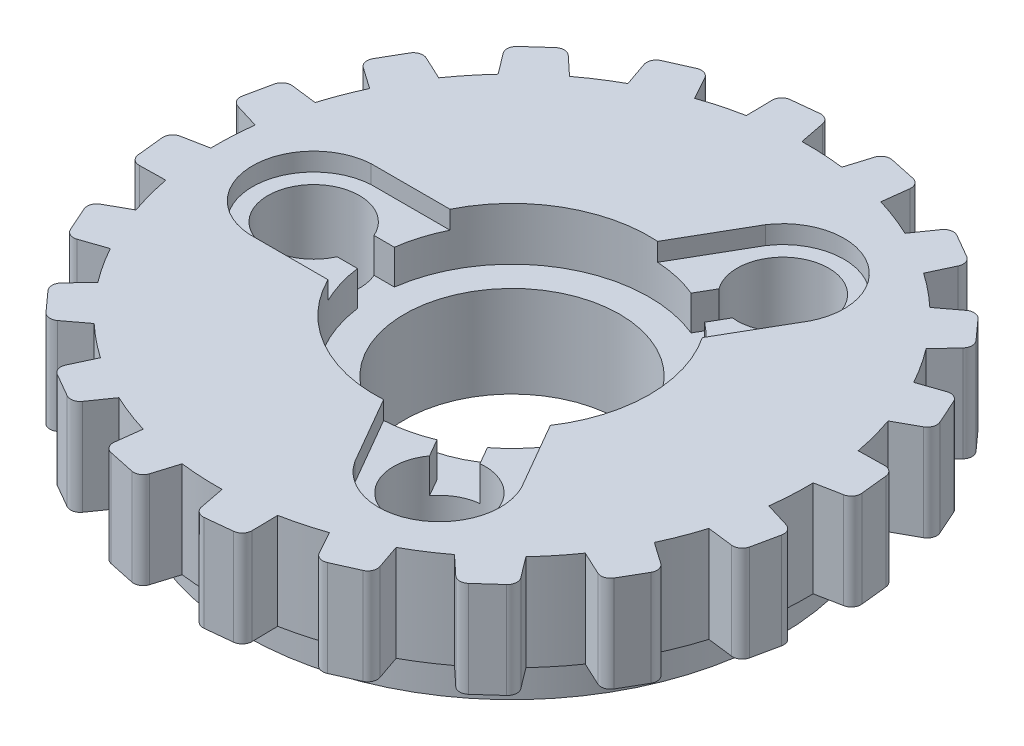
SolidWorks part; units mm, degrees
ref_plane "Front Plane" through (0, 0, 0) normal (0, 0, 1) x (1, 0, 0)
ref_plane "Top Plane" through (0, 0, 0) normal (0, 1, 0) x (1, 0, 0)
ref_plane "Right Plane" through (0, 0, 0) normal (1, 0, 0) x (0, 0, -1)
sketch "Sketch2" plane through (0, 0, 0) normal (0, 1, 0) x (1, 0, 0)
  circle A0 centre (0, 0) radius 30.764
  circle A1 centre (-20.6375, 0) radius 4.7625
  circle A2 centre (10.3187, 17.8726) radius 4.7625
  circle A3 centre (10.3187, -17.8726) radius 4.7625
  circle A5 centre (0, 0) radius 11.2
  point P11 (0, 0)
  dimension "D2" = 3
  dimension "D1" = 22.4
  dimension "D4" = 61.528
  dimension "D5" = 9.525
  dimension "D3" = 20.6375
extrude "Boss-Extrude2" add sketch "Sketch2" along normal blind 10
sketch "Sketch4" plane through (0, 0, 0) normal (0, -1, 0) x (1, 0, 0)
  circle A0 centre (10.3187, 17.8726) radius 4.7625 construction
  circle A1 centre (10.3187, 17.8726) radius 4.7625
  circle A2 centre (0, 0) radius 11.2
  circle A19 centre (0, 0) radius 27.7625
  point P6 (-1.3086, -0.0126)
  point P13 (12.187, -21.1085)
  point P15 (-24.374, 0)
  point P17 (12.187, 21.1085)
  point P18 (-12.5475, 0)
  point P25 (16.9495, -21.1085)
  point P26 (16.9495, 21.1085)
  point P27 (-26.7552, 4.1244)
  point P28 (9.8057, 25.2329)
  point P29 (9.8057, -25.2329)
  point P30 (-26.7552, -4.1244)
  point P31 (16.4175, -16.723)
  point P36 (16.4175, 16.723)
  point P46 (13.9118, 4.2533)
  circle M1 centre (10.3187, -17.8726) radius 4.7625
  circle M2 centre (-20.6375, 0) radius 4.7625
  circle M4 centre (0, 0) radius 11.2
  circle M5 centre (10.3187, 17.8726) radius 4.7625
  dimension "D1" = 22.4
extrude "Boss-Extrude3" add sketch "Sketch4" along normal blind 5 contours A19 M1 M5 M4 M2
sketch "Sketch5" plane through (0, 10, 0) normal (0, 1, 0) x (1, 0, 0)
  line L0 (-21, 6.35) -> (-9.2259, 6.35)
  line L1 (-21, -6.35) -> (-9.2259, -6.35)
  line L2 (5.0007, 21.3615) -> (-0.8863, 11.1649)
  line L3 (15.9993, 15.0115) -> (10.1122, 4.8149)
  line L4 (15.9993, -15.0115) -> (10.1122, -4.8149)
  line L5 (5.0007, -21.3615) -> (-0.8863, -11.1649)
  arc A2 (15.9993, 15.0115) -> (5.0007, 21.3615) centre (10.3188, 17.8726) ccw
  arc A4 (-21, 6.35) -> (-21, -6.35) centre (-20.6375, 0) ccw
  arc A5 (10.1122, 4.8149) -> (-0.8863, 11.1649) centre (0, 0) ccw
  circle A8 centre (-20.6375, 0) radius 4.7625 construction
  circle A10 centre (0, 0) radius 11.2 construction
  arc A11 (-9.2259, 6.35) -> (-9.2259, -6.35) centre (0, 0) ccw
  arc A12 (5.0007, -21.3615) -> (15.9993, -15.0115) centre (10.3187, -17.8726) ccw
  arc A13 (-0.8863, -11.1649) -> (10.1122, -4.8149) centre (0, 0) ccw
  point P9 (0, 0)
  point P23 (0, 0)
  dimension "D1" = 3
extrude "Cut-Extrude4" cut sketch "Sketch5" against normal blind 1.8875
sketch "Sketch7" plane through (0, 10, 0) normal (0, 1, 0) x (1, 0, 0)
  line L0 (5.4162, 13.2211) -> (6.4768, 15.0582)
  line L1 (8.7417, -11.3011) -> (9.8024, -13.1382)
  line L2 (9.8024, 13.1382) -> (8.7417, 11.3011)
  line L3 (10.1122, 4.8149) -> (15.9993, 15.0115) construction
  line L4 (6.4768, -15.0582) -> (5.4162, -13.2211)
  line L5 (-14.1579, -1.92) -> (-16.2792, -1.92)
  line L6 (-16.2792, 1.92) -> (-14.1579, 1.92)
  line L8 (5.0007, 21.3615) -> (-0.8863, 11.1649) construction
  arc A0 (5.4162, 13.2211) -> (-14.1579, 1.92) centre (0, 0) ccw
  arc A1 (9.8024, -13.1382) -> (6.4768, -15.0582) centre (10.3188, -17.8726) ccw
  arc A2 (-16.2792, -1.92) -> (-16.2792, 1.92) centre (-20.6375, 0) ccw
  circle A3 centre (10.3187, 17.8726) radius 4.7625 construction
  arc A6 (6.4768, 15.0582) -> (9.8024, 13.1382) centre (10.3187, 17.8726) ccw
  arc A8 (8.7417, -11.3011) -> (8.7417, 11.3011) centre (0, 0) ccw
  arc A10 (-14.1579, -1.92) -> (5.4162, -13.2211) centre (0, 0) ccw
  point P28 (0, 0)
  point P29 (0, 0)
  dimension "D1" = 28.575
  dimension "D3" = 4.43
  dimension "D4" = 4.43
  dimension "D2" = 3
extrude "Cut-Extrude7" cut sketch "Sketch7" against normal blind 5.48
sketch "Sketch8" plane through (0, 10, 0) normal (0, 1, 0) x (1, 0, 0)
  line L0 (0, 0) -> (26.6173, 46.1024) construction
  line L1 (5.0007, 21.3615) -> (0.9002, 14.2591) construction
  line L2 (2.3314, 34.1772) -> (21.2283, 23.2671) construction
  line L3 (13.0466, 27.8605) -> (14.6011, 30.0806)
  line L4 (15.9203, 30.3731) -> (18.3437, 28.9739)
  line L5 (17.6046, 25.229) -> (18.75, 27.6853)
  circle A0 centre (0, 0) radius 30.764 construction
  arc A1 (14.6011, 30.0806) -> (15.9203, 30.3731) centre (15.4203, 29.5071) cw
  arc A3 (18.75, 27.6853) -> (18.3437, 28.9739) centre (17.8437, 28.1079) ccw
  point P18 (17.132, 29.6735)
  point P124 (0, 0)
  dimension "D4" = 1
  dimension "D1" = 3.5
  dimension "D2" = 85
  dimension "D5" = 2.6316
extrude "Boss-Extrude4" add sketch "Sketch8" against normal up to surface (10 mm away) up to face at (0, 0, 30.764)
pattern_circular "CirPattern1" count 20 over 360 about axis through (0, 0, 0) along (0, 1, 0) of "Boss-Extrude4"
